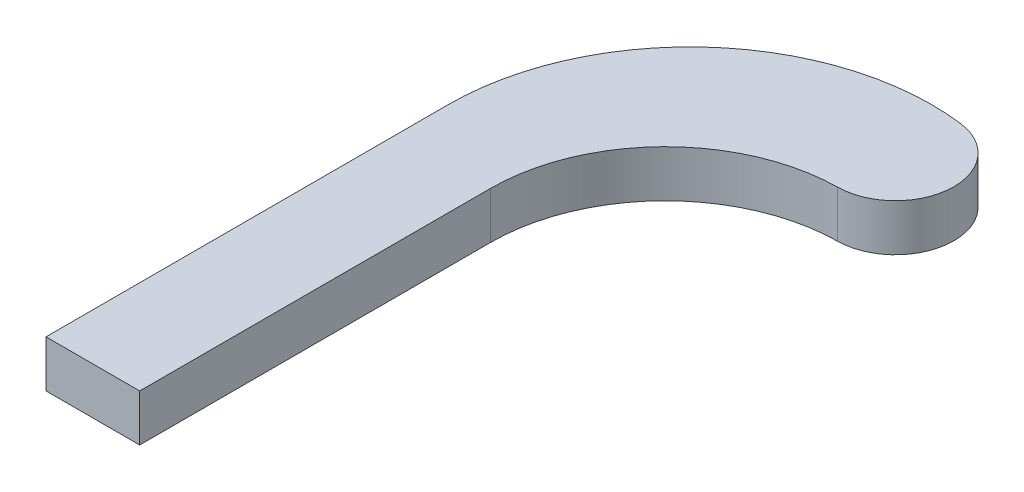
SolidWorks part; units mm, degrees
material "Pine"
ref_plane "Front Plane" through (0, 0, 0) normal (0, 0, 1) x (1, 0, 0)
ref_plane "Top Plane" through (0, 0, 0) normal (0, 1, 0) x (1, 0, 0)
ref_plane "Right Plane" through (0, 0, 0) normal (1, 0, 0) x (0, 0, -1)
sketch "Sketch1" plane through (0, 0, 0) normal (0, 1, 0) x (1, 0, 0)
  line L44 (-19.05, 142.605) -> (-19.05, 163.4734)
  line L48 (-19.05, 0) -> (19.05, 0)
  line L49 (-19.05, 0) -> (-19.05, 142.605)
  line L50 (-19.05, 142.605) -> (19.05, 142.605) construction
  line L51 (19.05, 0) -> (19.05, 142.605)
  arc A4 (19.05, 0) -> (-19.05, 0) centre (0, 0) cw construction
  arc A6 (-19.05, 163.4734) -> (91.9492, 261.05) centre (79.3382, 163.4734) cw
  arc A7 (19.05, 142.605) -> (89.2061, 213.6695) centre (90.1204, 142.605) cw
  arc A10 (89.2061, 213.6695) -> (91.9492, 261.05) centre (88.9, 237.4569) ccw
  point P4 (0, 0)
  dimension "D5" = 237.4569
  dimension "D2" = 88.9
  dimension "D4" = 98.3882
  dimension "D6" = 23.7894
  dimension "D3" = 71.0704
  dimension "D1" = 38.1
extrude "Boss-Extrude1" add sketch "Sketch1" along normal blind 19.05
